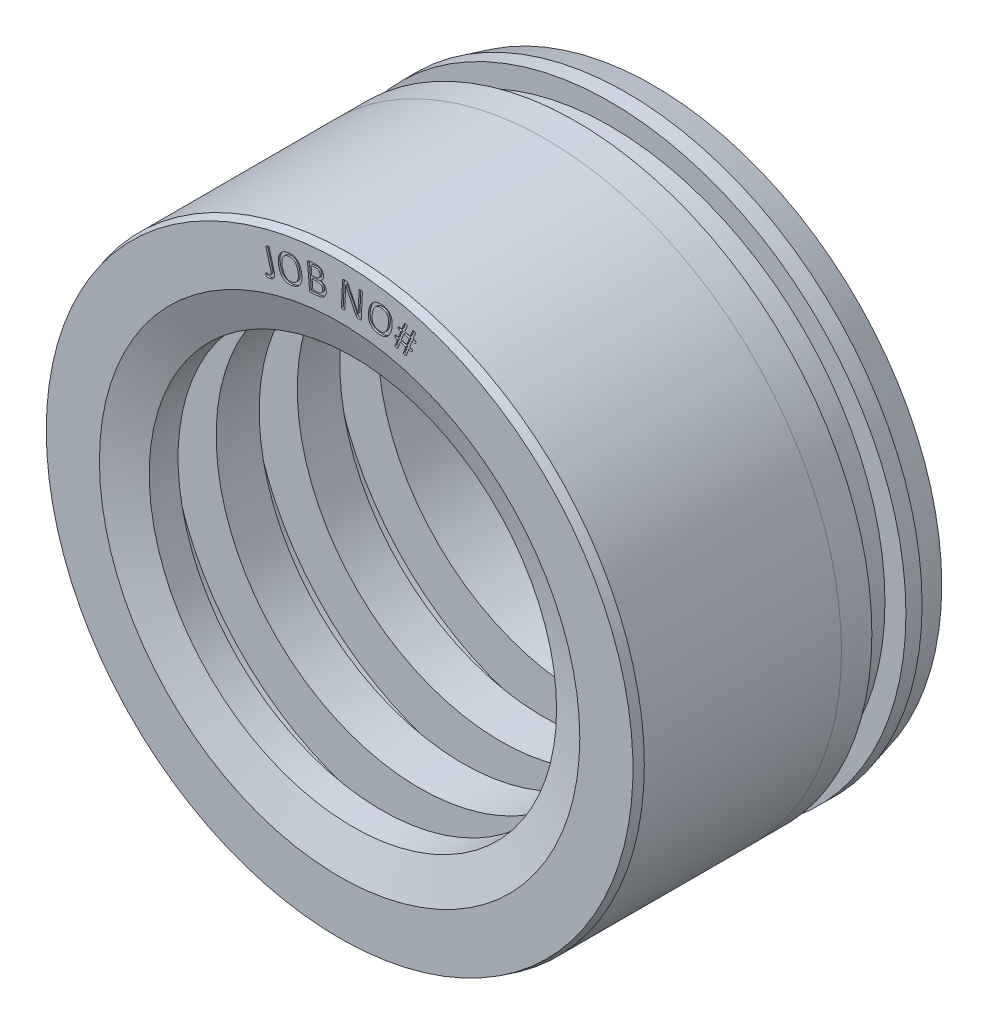
SolidWorks part; units mm, degrees
ref_plane "Front Plane" through (0, 0, 0) normal (0, 0, 1) x (1, 0, 0)
ref_plane "Top Plane" through (0, 0, 0) normal (0, 1, 0) x (1, 0, 0)
ref_plane "Right Plane" through (0, 0, 0) normal (1, 0, 0) x (0, 0, -1)
sketch "Sketch1" plane through (0, 0, 0) normal (1, 0, 0) x (0, 0, -1)
  line L0 (0, 0) -> (35, 0) construction
  line L1 (35, 32.1862) -> (32, 32.99)
  line L2 (0, 33) -> (23, 33)
  line L3 (0, 33) -> (0, 26.8)
  line L4 (1.4832, 22.725) -> (4.7, 22.725)
  line L5 (35, 32.1862) -> (35, 24.4571)
  line L6 (30.2, 32.99) -> (32, 32.99)
  line L8 (26.4, 32.99) -> (26.4, 30.65)
  line L9 (26.4, 30.65) -> (30.2, 30.65)
  line L10 (30.2, 32.99) -> (30.2, 30.65)
  line L11 (1.4832, 22.725) -> (0, 26.8)
  line L12 (8.95, 22.725) -> (13.75, 22.725)
  line L13 (22.75, 27.95) -> (27, 27.95)
  line L14 (22.75, 27.95) -> (22.75, 22.725)
  line L16 (27, 27.95) -> (27, 22.725)
  line L17 (13.75, 27.95) -> (18, 27.95)
  line L18 (13.75, 27.95) -> (13.75, 22.725)
  line L20 (18, 27.95) -> (18, 22.725)
  line L21 (4.7, 27.95) -> (8.95, 27.95)
  line L22 (4.7, 27.95) -> (4.7, 22.725)
  line L24 (8.95, 27.95) -> (8.95, 22.725)
  line L25 (18, 22.725) -> (22.75, 22.725)
  line L26 (27, 22.725) -> (34, 22.725)
  line L27 (35, 24.4571) -> (34, 22.725)
  line L28 (23, 33) -> (23, 32.99)
  line L29 (23, 32.99) -> (26.4, 32.99)
  point P4 (26.4, 31.82)
  dimension "D1" = 22.725
  dimension "D2" = 66
  dimension "D3" = 8.6
  dimension "D4" = 4.8
  dimension "D5" = 3
  dimension "D6" = 15
  dimension "D7" = 61.3
  dimension "D8" = 35
  dimension "D9" = 53.6
  dimension "D10" = 200
  dimension "D11" = 55.9
  dimension "D12" = 17
  dimension "D13" = 4.25
  dimension "D14" = 4.7
  dimension "D15" = 8
  dimension "D16" = 1
  dimension "D17" = 30
  dimension "D18" = 12
  dimension "D19" = 65.98
revolve "Revolve1" add sketch "Sketch1" angle 360 about L0
chamfer "Chamfer1" distance 1 angle 15 1 edges at (33, 0, 0)
sketch "Sketch2" plane through (0, 0, 0) normal (0, 0, 1) x (1, 0, 0)
  line L0 (0, 0) -> (-16.404, 28.3249) construction
  line L1 (-16.404, 28.3249) -> (0, 0) construction
  line L2 (0, 0) -> (16.4617, 28.6009) construction
  arc A0 (14.1005, 24.4984) -> (-14.166, 24.4606) centre (0, 0) ccw construction
  circle A2 centre (0, 0) radius 33 construction
  text T0 "JOB NO#" font "Calibri" height in points 11
  dimension "D3" = 28.2665
  dimension "D1" = 60
  dimension "D2" = 32.8657
extrude "Cut-Extrude1" cut sketch "Sketch2" against normal blind 0.2
